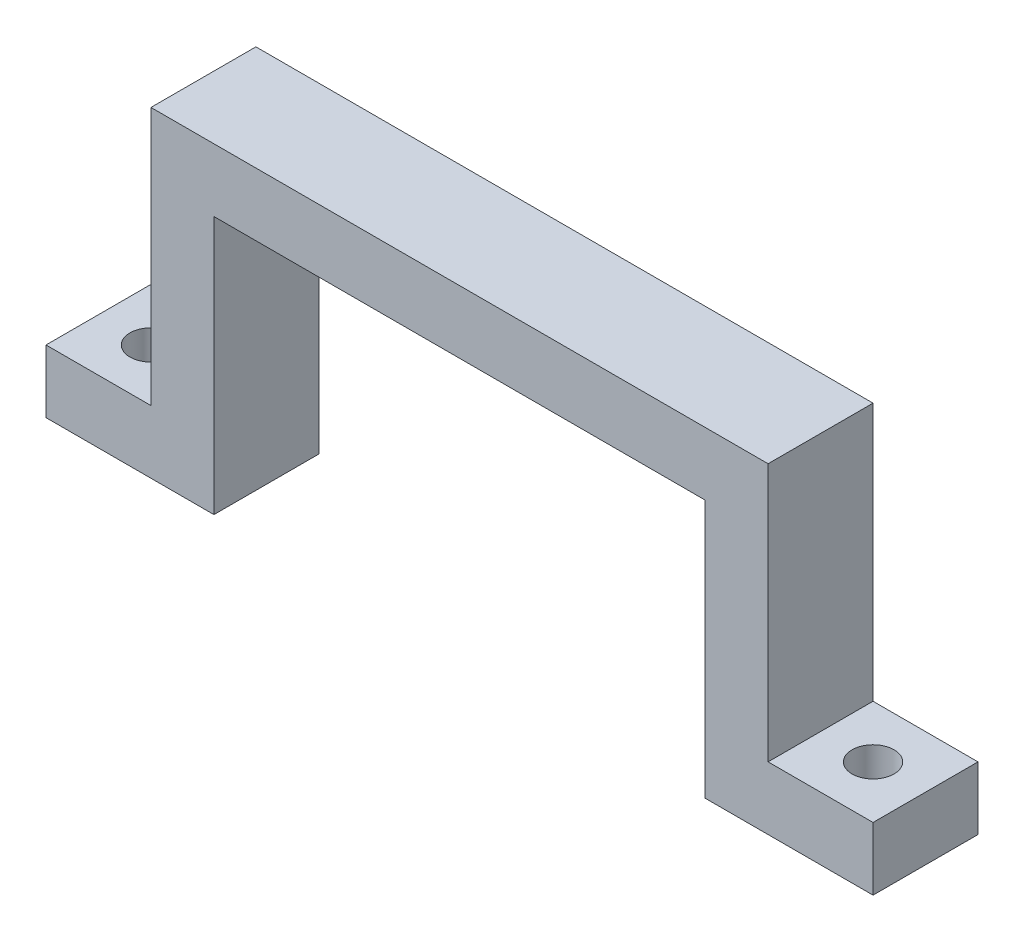
SolidWorks part; units mm, degrees
ref_plane "Front Plane" through (0, 0, 0) normal (0, 0, 1) x (1, 0, 0)
ref_plane "Top Plane" through (0, 0, 0) normal (0, 1, 0) x (1, 0, 0)
ref_plane "Right Plane" through (0, 0, 0) normal (1, 0, 0) x (0, 0, -1)
sketch "Sketch1" plane through (0, 0, 0) normal (0, 1, 0) x (1, 0, 0)
  line L1 (-14.7, 2.5) -> (14.7, 2.5)
  line L2 (-14.7, 2.5) -> (-14.7, -2.5)
  line L3 (-14.7, -2.5) -> (14.7, -2.5)
  line L4 (14.7, 2.5) -> (14.7, -2.5)
  line L5 (-14.7, 2.5) -> (14.7, -2.5) construction
  line L6 (-14.7, -2.5) -> (14.7, 2.5) construction
  point P0 (0, 0)
  dimension "D1" = 29.4
  dimension "D2" = 5
extrude "Boss-Extrude1" add sketch "Sketch1" against normal blind 15.3
sketch "Sketch4" plane through (0, 0, 2.5) normal (0, 0, 1) x (1, 0, 0)
  line L0 (-14.7, -15.3) -> (14.7, -15.3) construction
  line L1 (-11.7, -15.3) -> (11.7, -15.3)
  line L2 (-11.7, -15.3) -> (-11.7, -3)
  line L3 (-11.7, -3) -> (11.7, -3)
  line L4 (11.7, -15.3) -> (11.7, -3)
  line L5 (-14.7, -15.3) -> (-14.7, 0) construction
  line L6 (-14.7, 0) -> (14.7, 0) construction
  line L7 (14.7, -15.3) -> (14.7, 0) construction
  dimension "D1" = 3
  dimension "D2" = 3
  dimension "D3" = 3
extrude "Cut-Extrude2" cut sketch "Sketch4" against normal up to next
sketch "Sketch5" plane through (14.7, 0, 0) normal (1, 0, 0) x (0, 0, -1)
  line L0 (2.5, -15.3) -> (2.5, 0) construction
  line L1 (-2.5, -15.3) -> (2.5, -15.3)
  line L2 (-2.5, -15.3) -> (-2.5, -12.3)
  line L3 (-2.5, -12.3) -> (2.5, -12.3)
  line L4 (2.5, -15.3) -> (2.5, -12.3)
  dimension "D1" = 3
extrude "Boss-Extrude3" add sketch "Sketch5" along normal blind 5
sketch "Sketch6" plane through (0, -12.3, 0) normal (0, 1, 0) x (1, 0, 0)
  circle A1 centre (17.2, 0) radius 1
  dimension "D1" = 2
extrude "Cut-Extrude3" cut sketch "Sketch6" against normal up to next
mirror "Mirror2" about plane through (0, 0, 0) normal (1, 0, 0) of "Boss-Extrude3", "Cut-Extrude3"
